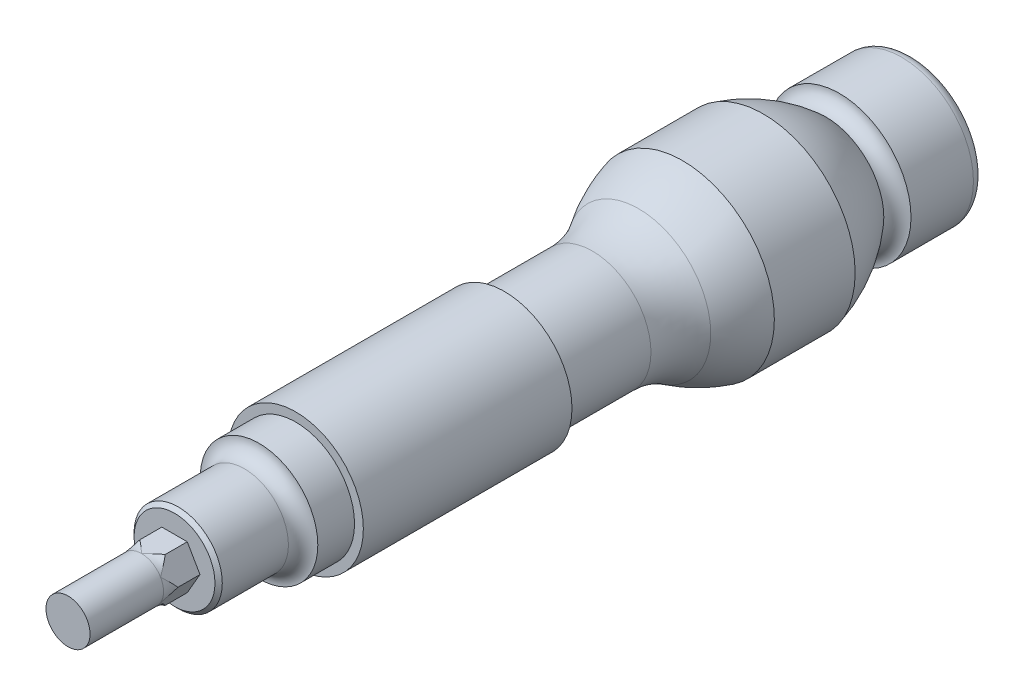
SolidWorks part; units mm, degrees
ref_plane "Front" through (0, 0, 0) normal (0, 0, 1) x (1, 0, 0)
ref_plane "Top" through (0, 0, 0) normal (0, 1, 0) x (1, 0, 0)
ref_plane "Right" through (0, 0, 0) normal (1, 0, 0) x (0, 0, -1)
sketch "Sketch1" plane through (0, 0, 0) normal (0, 1, 0) x (1, 0, 0)
  line L0 (0, 0) -> (0, 100.5)
  line L1 (0, 100.5) -> (9.75, 100.5)
  line L2 (9.75, 100.5) -> (9.75, 90.5)
  line L3 (12.5, 80.15) -> (12.5, 69.15)
  line L4 (7.96, 44.9) -> (9.2, 44.9)
  line L5 (9.2, 44.9) -> (9.2, 16.5)
  line L6 (9.2, 16.5) -> (8, 16.5)
  line L7 (8, 16.5) -> (8, 11.5)
  line L8 (6, 9.5) -> (6, 0)
  line L9 (6, 0) -> (0, 0)
  line L10 (7.9, 88.65) -> (7.9, 82.7301) construction
  line L11 (7.96, 44.9) -> (7.96, 56.8919)
  arc A0 (9.75, 90.5) -> (7.9, 88.65) centre (9.75, 88.65) ccw
  arc A1 (7.9, 88.65) -> (12.5, 80.15) centre (-7.8163, 74.65) cw
  arc A2 (12.5, 69.15) -> (9.8225, 63.1663) centre (-7.8163, 74.65) cw
  arc A3 (7.96, 56.8919) -> (9.8225, 63.1663) centre (19.46, 56.8919) cw
  arc A4 (8, 11.5) -> (6, 9.5) centre (8, 9.5) ccw
  point P10 (0, 0)
  point P12 (7.96, 60.5294)
  dimension "D15" = 11.5
  dimension "D1" = 100.5
  dimension "D2" = 9.75
  dimension "D3" = 12.5
  dimension "D4" = 10
  dimension "D5" = 7.9
  dimension "D6" = 11
  dimension "D7" = 7.96
  dimension "D8" = 6
  dimension "D9" = 8
  dimension "D10" = 9.5
  dimension "D11" = 5
  dimension "D12" = 9.2
  dimension "D13" = 28.4
  dimension "D14" = 8.5
revolve "Revolve1" add sketch "Sketch1" angle 360 about L0
fillet "Fillet1" radius 1.5 1 edges at (9.75, 0, -100.5)
chamfer "Chamfer1" distance 0.5 angle 45 1 edges at (6, 0, 0)
sketch "Sketch2" plane through (0, 0, 0) normal (0, 0, 1) x (1, 0, 0)
  line L1 (1.7321, 3) -> (-1.7321, 3)
  line L2 (-1.7321, 3) -> (-3.4641, 0)
  line L3 (-3.4641, 0) -> (-1.7321, -3)
  line L4 (-1.7321, -3) -> (1.7321, -3)
  line L5 (1.7321, -3) -> (3.4641, 0)
  line L6 (3.4641, 0) -> (1.7321, 3)
  circle A0 centre (0, 0) radius 3 construction
  dimension "D1" = 6
extrude "Boss-Extrude1" add sketch "Sketch2" along normal blind 14.5
sketch "Sketch3" plane through (0, 0, 0) normal (0, 1, 0) x (1, 0, 0)
  line L0 (3, -14.5) -> (3, -4.5)
  line L1 (3.4641, -14.5) -> (1.7321, -14.5) construction
  line L2 (3.4641, -14.5) -> (3.4641, 0) construction
  line L3 (3.4641, -3) -> (3.4641, -14.5)
  line L4 (3.4641, -14.5) -> (3, -14.5)
  arc A0 (3, -4.5) -> (3.4641, -3) centre (5.6561, -4.5) cw
  dimension "D1" = 3
  dimension "D2" = 10
  dimension "D3" = 1.5
revolve "Cut-Revolve1" cut sketch "Sketch3" angle 360 about axis through (0, 0, 0) along (0, 0, 1)
